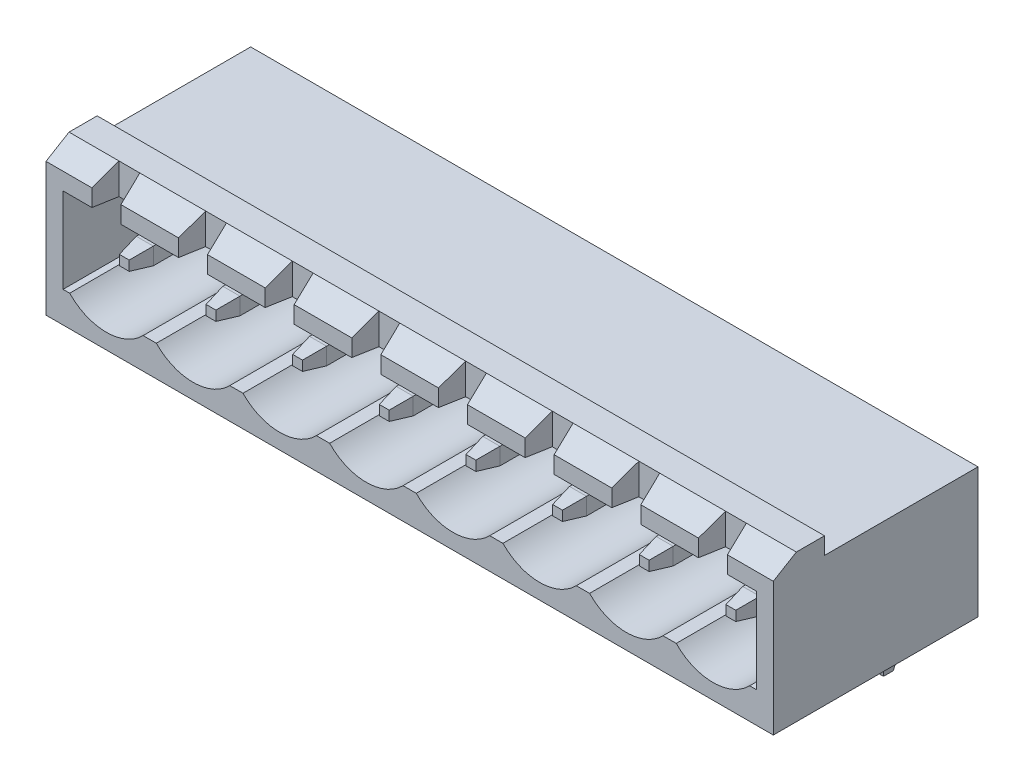
SolidWorks part; units mm, degrees
ref_plane "Front Plane" through (0, 0, 0) normal (0, 0, 1) x (1, 0, 0)
ref_plane "Top Plane" through (0, 0, 0) normal (0, 1, 0) x (1, 0, 0)
ref_plane "Right Plane" through (0, 0, 0) normal (1, 0, 0) x (0, 0, -1)
sketch "Sketch1" plane through (0, 0, 0) normal (0, 0, 1) x (1, 0, 0)
  line L1 (21.32, -3.81) -> (-21.32, -3.81)
  line L2 (21.32, -3.81) -> (21.32, 3.81)
  line L3 (21.32, 3.81) -> (-21.32, 3.81)
  line L4 (-21.32, -3.81) -> (-21.32, 3.81)
  line L5 (21.32, -3.81) -> (-21.32, 3.81) construction
  line L6 (21.32, 3.81) -> (-21.32, -3.81) construction
  point P0 (0, 0)
  dimension "D1" = 7.62
  dimension "D2" = 42.64
extrude "Boss-Extrude1" add sketch "Sketch1" along normal mid plane 12
sketch "Sketch7" plane through (21.32, 0, 0) normal (1, 0, 0) x (0, 0, -1)
  line L0 (-6, 3.81) -> (-6, 4)
  line L1 (-3, 4.81) -> (-6, 4.81) construction
  line L2 (-3, 4.81) -> (-3, 3.81) construction
  line L3 (-3, 3.81) -> (-6, 3.81) construction
  line L4 (-6, 4.81) -> (-6, 3.81) construction
  line L5 (-3, 4.81) -> (-6, 3.81) construction
  line L6 (-3, 3.81) -> (-6, 4.81) construction
  line L7 (-6, 4) -> (-4.65, 4.81)
  line L8 (-4.65, 4.81) -> (-3, 4.81)
  line L9 (-3, 4.81) -> (-3, 3.81)
  line L10 (-3, 3.81) -> (-6, 3.81)
  point P0 (-4.5, 4.31)
  point P6 (0, 0)
  dimension "D1" = 1
  dimension "D2" = 3
  dimension "D3" = 1.65
  dimension "D4" = 0.81
extrude "Boss-Extrude6" add sketch "Sketch7" against normal up to surface (42.64 mm away) up to face at (-21.32, 0, 0)
sketch "Sketch2" plane through (0, 0, 6) normal (0, 0, 1) x (1, 0, 0)
  line L0 (21.32, -3.81) -> (21.32, 4) construction
  line L1 (20.32, -2) -> (15.24, -2) construction
  line L2 (20.32, -2) -> (20.32, 3) construction
  line L3 (20.32, 3) -> (15.24, 3) construction
  line L4 (15.24, -2) -> (15.24, 3) construction
  line L5 (20.32, -2) -> (15.24, 3) construction
  line L6 (20.32, 3) -> (15.24, -2) construction
  line L7 (21.32, 3.81) -> (-21.32, 3.81) construction
  line L8 (-21.32, -3.81) -> (21.32, -3.81) construction
  line L9 (15.6278, -2) -> (15.24, -2)
  line L10 (15.24, -2) -> (15.24, 3)
  line L11 (15.24, 3) -> (20.32, 3)
  line L12 (20.32, 3) -> (20.32, -2)
  line L13 (20.32, -2) -> (19.9322, -2)
  arc A0 (15.6278, -2) -> (19.9322, -2) centre (17.78, 0.09) ccw
  point P0 (17.78, 0.5)
  point P15 (17.78, -2.91)
  dimension "D7" = 3
  dimension "D1" = 3.54
  dimension "D2" = 5.08
  dimension "D3" = 0.81
  dimension "D4" = 1.81
  dimension "D5" = 5
  dimension "D6" = 0.9
extrude "Cut-Extrude1" cut sketch "Sketch2" against normal blind 11.2
sketch "Sketch3" plane through (0, 0, -5.2) normal (0, 0, 1) x (1, 0, 0)
  line L0 (16.78, -1.028) -> (16.78, -2.7384)
  line L1 (18.78, -1.028) -> (18.78, -2.7384)
  line L2 (17.78, 0.09) -> (17.78, -0.91) construction
  line L3 (16.301, -0.16) -> (15.24, -0.16)
  line L4 (15.24, 3) -> (15.24, -2) construction
  line L5 (16.301, 0.34) -> (15.24, 0.34)
  line L6 (15.24, 0.34) -> (15.24, -0.16)
  line L7 (19.259, -0.16) -> (20.32, -0.16)
  line L8 (20.32, -2) -> (20.32, 3) construction
  line L9 (20.32, -0.16) -> (20.32, 0.34)
  line L10 (20.32, 0.34) -> (19.259, 0.34)
  line L11 (16.28, 0.09) -> (18.78, 0.09) construction
  line L12 (17.53, 1.569) -> (17.53, 3)
  line L13 (20.32, 3) -> (15.24, 3) construction
  line L14 (17.53, 3) -> (18.03, 3)
  line L15 (18.03, 3) -> (18.03, 1.569)
  line L16 (-21.32, -3.81) -> (21.32, -3.81) construction
  line L17 (17.78, -0.91) -> (17.78, -1.41) construction
  line L18 (17.78, -1.41) -> (17.78, -2.91) construction
  line L19 (18.78, 0.09) -> (19.28, 0.09) construction
  line L20 (19.28, 0.09) -> (20.32, 0.09) construction
  line L21 (15.24, 0.09) -> (16.28, 0.09) construction
  arc A0 (15.6278, -2) -> (19.9322, -2) centre (17.78, 0.09) ccw construction
  arc A1 (16.78, -2.7384) -> (18.78, -2.7384) centre (17.78, 0.09) ccw
  circle A2 centre (17.78, 0.09) radius 1 construction
  arc A3 (18.78, -1.028) -> (19.259, -0.16) centre (17.78, 0.09) ccw
  arc A4 (16.78, -1.028) -> (17.78, -1.41) centre (17.78, 0.09) ccw construction
  arc A5 (17.78, -1.41) -> (18.78, -1.028) centre (17.78, 0.09) ccw construction
  arc A6 (19.259, -0.16) -> (19.28, 0.09) centre (17.78, 0.09) ccw construction
  arc A7 (19.259, 0.34) -> (18.03, 1.569) centre (17.78, 0.09) ccw
  arc A8 (19.28, 0.09) -> (19.259, 0.34) centre (17.78, 0.09) ccw construction
  arc A9 (18.03, 1.569) -> (17.53, 1.569) centre (17.78, 0.09) ccw construction
  arc A10 (17.53, 1.569) -> (16.301, 0.34) centre (17.78, 0.09) ccw
  arc A11 (16.301, 0.34) -> (16.28, 0.09) centre (17.78, 0.09) ccw construction
  arc A12 (16.301, -0.16) -> (16.78, -1.028) centre (17.78, 0.09) ccw
  arc A13 (16.28, 0.09) -> (16.301, -0.16) centre (17.78, 0.09) ccw construction
  arc A14 (15.6278, -2) -> (16.78, -2.7384) centre (17.78, 0.09) ccw construction
  arc A15 (18.78, -2.7384) -> (19.9322, -2) centre (17.78, 0.09) ccw construction
  dimension "D1" = 2
  dimension "D2" = 3
  dimension "D3" = 2
  dimension "D4" = 0.5
  dimension "D5" = 0.5
  dimension "D6" = 3.9
  dimension "D7" = 3
extrude "Boss-Extrude2" add sketch "Sketch3" along normal blind 2.5
sketch "Sketch4" plane through (0, 0, -2.7) normal (0, 0, 1) x (1, 0, 0)
  circle A1 centre (17.78, 0.09) radius 1
  dimension "D1" = 2
extrude "Boss-Extrude3" add sketch "Sketch4" along normal offset from surface (0.7 mm away) 8
sketch "Sketch5" plane through (0, 0, -2) normal (0, 0, 1) x (1, 0, 0)
  line L1 (18.28, -0.41) -> (17.28, -0.41)
  line L2 (18.28, -0.41) -> (18.28, 0.59)
  line L3 (18.28, 0.59) -> (17.28, 0.59)
  line L4 (17.28, -0.41) -> (17.28, 0.59)
  line L5 (18.28, -0.41) -> (17.28, 0.59) construction
  line L6 (18.28, 0.59) -> (17.28, -0.41) construction
  point P0 (17.78, 0.09)
  dimension "D1" = 1
extrude "Boss-Extrude4" add sketch "Sketch5" along normal blind 5.75 separate body
sketch "Sketch6" plane through (0, 0, 3.75) normal (0, 0, 1) x (1, 0, 0)
  line L4 (17.28, 0.59) -> (17.28, -0.41)
  line L5 (17.28, -0.41) -> (18.28, -0.41)
  line L6 (18.28, -0.41) -> (18.28, 0.59)
  line L7 (18.28, 0.59) -> (17.28, 0.59)
  line L8 (17.28, 0.59) -> (17.28, -0.41)
  line L9 (17.28, -0.41) -> (18.28, -0.41)
  line L10 (18.28, -0.41) -> (18.28, 0.59)
  line L11 (18.28, 0.59) -> (17.28, 0.59)
  dimension "D1" = 0
extrude "Boss-Extrude5" add sketch "Sketch6" along normal blind 1.2 draft 10
sketch "Sketch9" plane through (0, 4.81, 0) normal (0, 1, 0) x (1, 0, 0)
  line L0 (17.78, 5.2) -> (17.78, -6) construction
  line L1 (20.32, -6) -> (15.24, -6) construction
  line L2 (16.93, -6) -> (17.17, -4.65)
  line L3 (-21.32, -4.65) -> (21.32, -4.65) construction
  line L4 (17.17, -4.65) -> (18.39, -4.65)
  line L5 (18.39, -4.65) -> (18.63, -6)
  line L6 (18.63, -6) -> (16.93, -6)
  point P2 (17.78, -4.65)
  dimension "D1" = 1.22
  dimension "D2" = 1.7
extrude "Cut-Extrude2" cut sketch "Sketch9" against normal up to next
sketch "Sketch10" plane through (0, -3.81, 0) normal (0, -1, 0) x (1, 0, 0)
  line L0 (17.78, -6) -> (17.78, 6) construction
  line L1 (-21.32, -6) -> (21.32, -6) construction
  line L2 (-21.32, 6) -> (21.32, 6) construction
  line L4 (17.28, -4.5) -> (18.28, -4.5)
  line L5 (17.28, -4.5) -> (17.28, -3.5)
  line L6 (17.28, -3.5) -> (18.28, -3.5)
  line L7 (18.28, -4.5) -> (18.28, -3.5)
  line L8 (17.28, -4.5) -> (18.28, -3.5) construction
  line L9 (17.28, -3.5) -> (18.28, -4.5) construction
  point P7 (17.78, -4)
  dimension "D1" = 10
  dimension "D2" = 1
extrude "Boss-Extrude7" add sketch "Sketch10" along normal blind 2.3 separate body
sketch "Sketch11" plane through (0, -6.11, 0) normal (0, -1, 0) x (1, 0, 0)
  line L4 (18.28, -4.5) -> (18.28, -3.5)
  line L5 (18.28, -3.5) -> (17.28, -3.5)
  line L6 (17.28, -3.5) -> (17.28, -4.5)
  line L7 (17.28, -4.5) -> (18.28, -4.5)
  line L8 (18.28, -4.5) -> (18.28, -3.5)
  line L9 (18.28, -3.5) -> (17.28, -3.5)
  line L10 (17.28, -3.5) -> (17.28, -4.5)
  line L11 (17.28, -4.5) -> (18.28, -4.5)
  dimension "D1" = 0
extrude "Boss-Extrude8" add sketch "Sketch11" along normal blind 1.2 draft 10
sketch "Sketch12" plane through (0, 0, -6) normal (0, 0, -1) x (-1, 0, 0)
  line L0 (-17.78, 0.09) -> (-17.78, -0.91) construction
  line L1 (-16.78, -3.81) -> (-18.78, -3.81)
  line L2 (-16.78, -3.81) -> (-16.78, 2.94)
  line L3 (-16.78, 2.94) -> (-18.78, 2.94)
  line L4 (-18.78, -3.81) -> (-18.78, 2.94)
  line L5 (-16.78, -3.81) -> (-18.78, 2.94) construction
  line L6 (-16.78, 2.94) -> (-18.78, -3.81) construction
  line L7 (21.32, -3.81) -> (-21.32, -3.81) construction
  point P0 (-17.78, -0.435)
  point P5 (0, 0)
  dimension "D1" = 6.75
  dimension "D2" = 2
extrude "Cut-Extrude3" cut sketch "Sketch12" against normal blind 0.5
pattern_linear "LPattern1" count 8 spacing 5.08 along (-1, 0, 0) of "Cut-Extrude1", "Boss-Extrude2", "Boss-Extrude3", "Cut-Extrude2", "Cut-Extrude3"
pattern_linear "LPattern2" count 8 spacing 5.08 along (-1, 0, 0) of bodies 111 106
equation "\"NumPins\"= 8'Number of pins on block"
equation "\"PinPitch\"= .2in'distance between pin centers"
equation "\"TerminalHeight\"= .3in'height of block"
equation "\"TerminalDepth\"= 12mm'depth of block"
equation "\"SideOffset\"= 1mm'offset on edges to provide space for side walls"
equation "\"PinSize\"= 1mm'side length of pin square profile"
equation "\"TerminalWidth\"= ( 2 * \"SideOffset\" ) + ( \"NumPins\" * \"PinPitch\" )"
equation "\"D2@Sketch1\"=\"NumPins\"*\"PinPitch\"+2*\"SideOffset\""
equation "\"D3@LPattern1\"=\"PinPitch\""
equation "\"D1@LPattern1\"=\"NumPins\""
equation "\"D2@Sketch10\"=\"PinSize\""
equation "\"D3@LPattern2\"=\"PinPitch\""
equation "\"D1@LPattern2\"=\"NumPins\""
